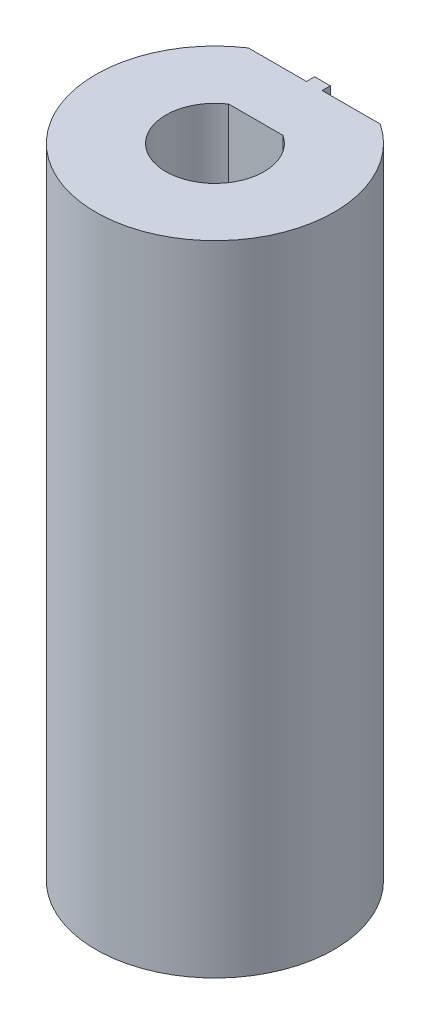
SolidWorks part; units mm, degrees
ref_plane "前视基准面" through (0, 0, 0) normal (0, 0, 1) x (1, 0, 0)
ref_plane "上视基准面" through (0, 0, 0) normal (0, 1, 0) x (1, 0, 0)
ref_plane "右视基准面" through (0, 0, 0) normal (1, 0, 0) x (0, 0, -1)
sketch "草图1" plane through (0, 0, 0) normal (0, 1, 0) x (1, 0, 0)
  line L0 (-0.8292, 1.25) -> (0.8292, 1.25)
  line L1 (-0.2401, 3.0338) -> (-2.0124, 3.0338)
  line L2 (0, 3.0338) -> (0, 4.0985) construction
  line L3 (0, 3.0338) -> (0, 3.2838)
  line L4 (0.2401, 3.2838) -> (-0.2401, 3.2838)
  line L5 (-0.2401, 3.2838) -> (-0.2401, 3.0338)
  line L6 (0.2401, 3.2838) -> (0.2401, 3.0338)
  line L7 (0.2401, 3.0338) -> (2.0124, 3.0338)
  arc A0 (-0.8292, 1.25) -> (0.8292, 1.25) centre (0, 0) ccw
  arc A2 (-2.0124, 3.0338) -> (2.0124, 3.0338) centre (0, 0) ccw
  point P7 (0, 1.25)
  point P10 (0, 3.0338)
  point P15 (0, 3.2838)
  dimension "D1" = 0.25
  dimension "D2" = 1.5
extrude "凸台-拉伸1" add sketch "草图1" along normal blind 19.5
